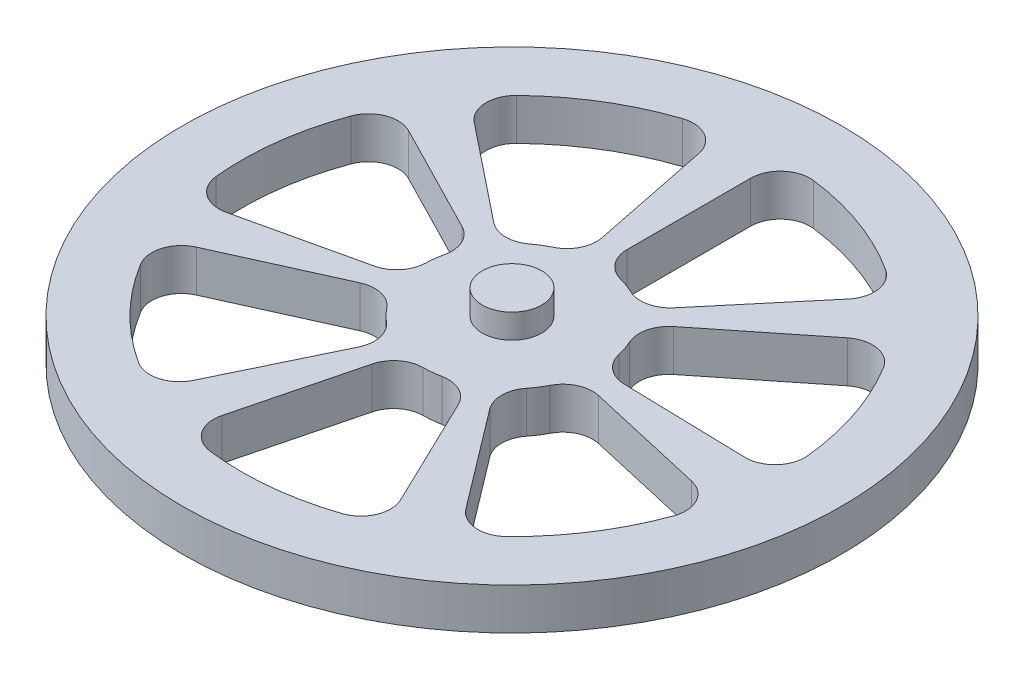
SolidWorks part; units mm, degrees
ref_plane "Front Plane" through (0, 0, 0) normal (0, 0, 1) x (1, 0, 0)
ref_plane "Top Plane" through (0, 0, 0) normal (0, 1, 0) x (1, 0, 0)
ref_plane "Right Plane" through (0, 0, 0) normal (1, 0, 0) x (0, 0, -1)
sketch "Sketch1" plane through (0, 0, 0) normal (0, 1, 0) x (1, 0, 0)
  circle A0 centre (0, 0) radius 55.5
  dimension "D1" = 111
extrude "Boss-Extrude1" add sketch "Sketch1" along normal blind 7
sketch "Sketch2" plane through (0, 7, 0) normal (0, 1, 0) x (1, 0, 0)
  line L0 (0, 15) -> (0, 45.5)
  line L1 (9.6418, 11.4907) -> (29.2468, 34.855)
  arc A0 (9.6418, 11.4907) -> (0, 15) centre (0, 0) ccw
  arc A1 (29.2468, 34.855) -> (0, 45.5) centre (0, 0) ccw
  circle A2 centre (0, 0) radius 55.5 construction
  dimension "D1" = 15
  dimension "D2" = 10
  dimension "D3" = 40
extrude "Cut-Extrude1" cut sketch "Sketch2" against normal blind 7
fillet "Fillet1" radius 5 4 edges at (29.2468, 3.5, -34.855) (0, 3.5, -45.5) (9.6418, 3.5, -11.4907) (0, 3.5, -15)
pattern_circular "CirPattern1" count 7 over 360 about axis through (0, 0, 0) along (0, 1, 0) of "Cut-Extrude1", "Fillet1"
sketch "Sketch3" plane through (0, 7, 0) normal (0, 1, 0) x (1, 0, 0)
  circle A0 centre (0, 0) radius 5
  dimension "D1" = 10
extrude "Boss-Extrude2" add sketch "Sketch3" along normal blind 4.1
